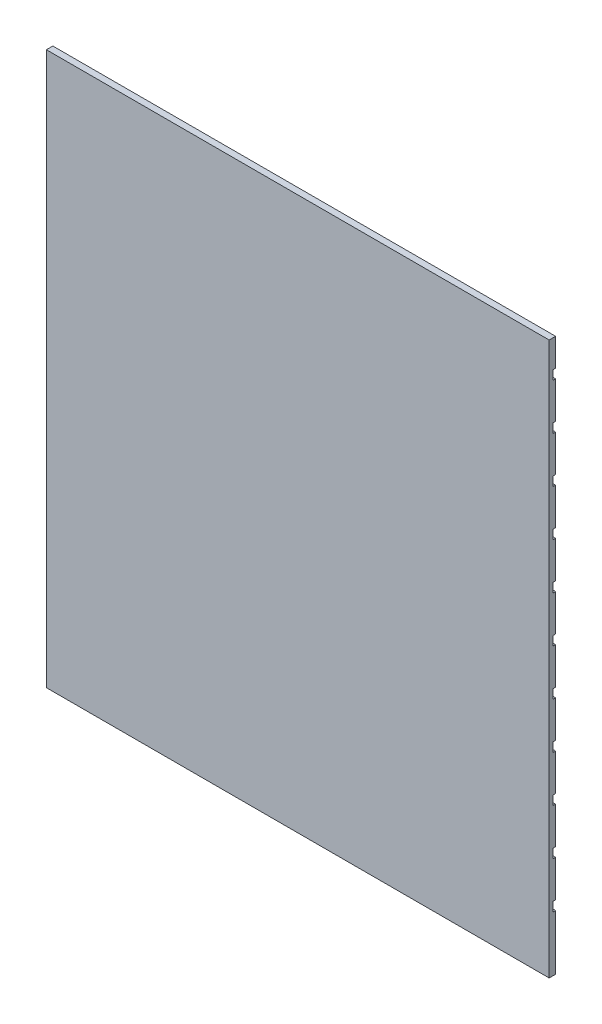
SolidWorks part; units mm, degrees
ref_plane "Front Plane" through (0, 0, 0) normal (0, 0, 1) x (1, 0, 0)
ref_plane "Top Plane" through (0, 0, 0) normal (0, 1, 0) x (1, 0, 0)
ref_plane "Right Plane" through (0, 0, 0) normal (1, 0, 0) x (0, 0, -1)
sketch "Sketch2" plane through (0, 0, 0) normal (1, 0, 0) x (0, 0, -1)
  line L1 (0, 0) -> (17.78, 0)
  line L2 (0, 0) -> (0, -1524)
  line L3 (0, -1524) -> (17.78, -1524)
  line L4 (17.78, 0) -> (17.78, -1524)
  dimension "D1" = 17.78
  dimension "D2" = 1524
extrude "Boss-Extrude1" add sketch "Sketch2" along normal blind 1386.84
sketch "Sketch3" plane through (0, 0, -17.78) normal (0, 0, -1) x (-1, 0, 0)
  line L0 (-1386.84, -1524) -> (-1386.84, 0) construction
  line L1 (-1386.84, -76.2) -> (0, -76.2)
  line L2 (-1386.84, -76.2) -> (-1386.84, -101.6)
  line L3 (-1386.84, -101.6) -> (0, -101.6)
  line L4 (0, -76.2) -> (0, -101.6)
  line L5 (0, -1524) -> (0, 0) construction
  line L6 (-1386.84, 0) -> (0, 0) construction
  line L7 (-1386.84, -228.6) -> (0, -228.6)
  line L8 (-1386.84, -203.2) -> (0, -203.2)
  line L9 (-1386.84, -203.2) -> (-1386.84, -228.6)
  line L10 (0, -203.2) -> (0, -228.6)
  line L11 (-1386.84, -355.6) -> (0, -355.6)
  line L12 (-1386.84, -330.2) -> (0, -330.2)
  line L13 (-1386.84, -330.2) -> (-1386.84, -355.6)
  line L14 (0, -330.2) -> (0, -355.6)
  line L15 (-1386.84, -482.6) -> (0, -482.6)
  line L16 (-1386.84, -457.2) -> (0, -457.2)
  line L17 (-1386.84, -457.2) -> (-1386.84, -482.6)
  line L18 (0, -457.2) -> (0, -482.6)
  line L19 (-1386.84, -609.6) -> (0, -609.6)
  line L20 (-1386.84, -584.2) -> (0, -584.2)
  line L21 (-1386.84, -584.2) -> (-1386.84, -609.6)
  line L22 (0, -584.2) -> (0, -609.6)
  line L23 (-1386.84, -736.6) -> (0, -736.6)
  line L24 (-1386.84, -711.2) -> (0, -711.2)
  line L25 (-1386.84, -711.2) -> (-1386.84, -736.6)
  line L26 (0, -711.2) -> (0, -736.6)
  line L27 (-1386.84, -863.6) -> (0, -863.6)
  line L28 (-1386.84, -838.2) -> (0, -838.2)
  line L29 (-1386.84, -838.2) -> (-1386.84, -863.6)
  line L30 (0, -838.2) -> (0, -863.6)
  line L31 (-1386.84, -990.6) -> (0, -990.6)
  line L32 (-1386.84, -965.2) -> (0, -965.2)
  line L33 (-1386.84, -965.2) -> (-1386.84, -990.6)
  line L34 (0, -965.2) -> (0, -990.6)
  line L35 (-1386.84, -1117.6) -> (0, -1117.6)
  line L36 (-1386.84, -1092.2) -> (0, -1092.2)
  line L37 (-1386.84, -1092.2) -> (-1386.84, -1117.6)
  line L38 (0, -1092.2) -> (0, -1117.6)
  line L39 (-1386.84, -1244.6) -> (0, -1244.6)
  line L40 (-1386.84, -1219.2) -> (0, -1219.2)
  line L41 (-1386.84, -1219.2) -> (-1386.84, -1244.6)
  line L42 (0, -1219.2) -> (0, -1244.6)
  line L43 (-1386.84, -1371.6) -> (0, -1371.6)
  line L44 (-1386.84, -1346.2) -> (0, -1346.2)
  line L45 (-1386.84, -1346.2) -> (-1386.84, -1371.6)
  line L46 (0, -1346.2) -> (0, -1371.6)
  dimension "D1" = 25.4
  dimension "D2" = 76.2
  dimension "D3" = 11
extrude "Cut-Extrude1" cut sketch "Sketch3" against normal blind 7.62
